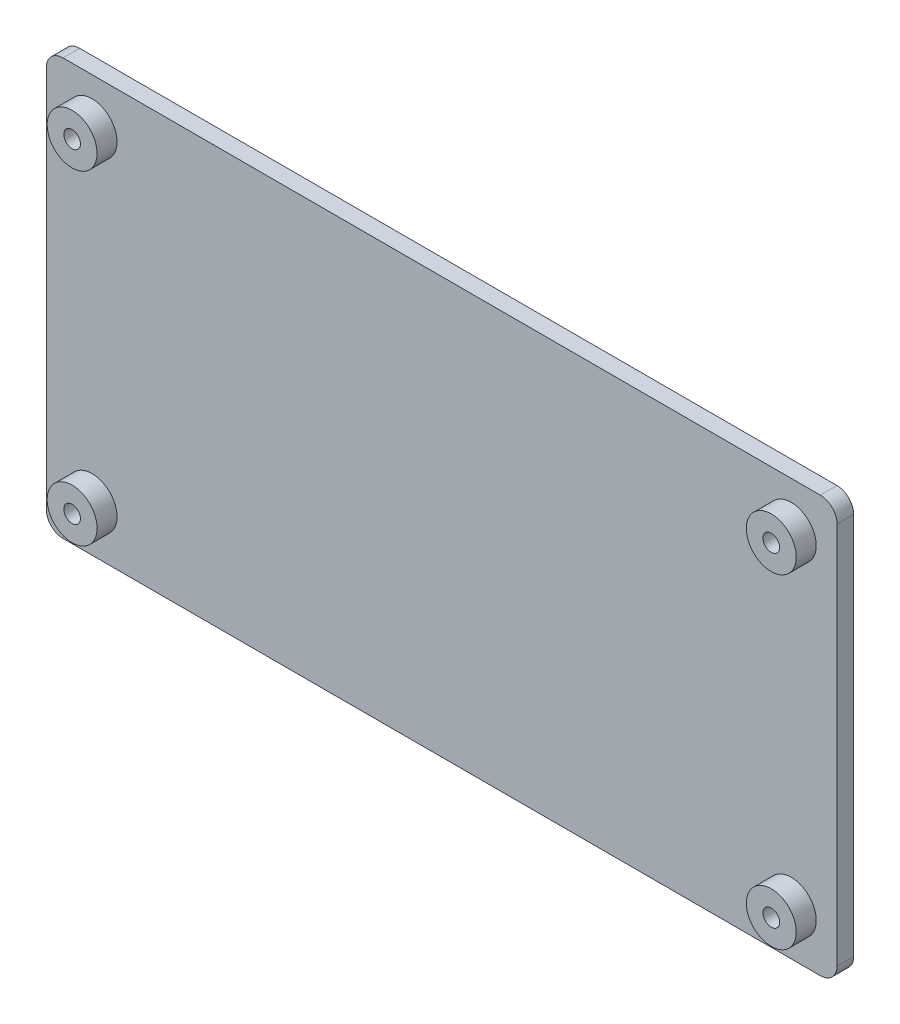
SolidWorks part; units mm, degrees
ref_plane "前视基准面" through (0, 0, 0) normal (0, 0, 1) x (1, 0, 0)
ref_plane "上视基准面" through (0, 0, 0) normal (0, 1, 0) x (1, 0, 0)
ref_plane "右视基准面" through (0, 0, 0) normal (1, 0, 0) x (0, 0, -1)
sketch "草图1" plane through (0, 0, 0) normal (0, 0, 1) x (1, 0, 0)
  line L1 (-47.5, -25) -> (47.5, -25)
  line L2 (-47.5, -25) -> (-47.5, 25)
  line L3 (-47.5, 25) -> (47.5, 25)
  line L4 (47.5, -25) -> (47.5, 25)
  line L5 (0, 25) -> (0, -25) construction
  line L6 (-47.5, 0) -> (47.5, 0) construction
  point P0 (0, 0)
extrude "凸台-拉伸1" add sketch "草图1" along normal blind 2
sketch "草图3" plane through (0, 0, 0) normal (0, 0, -1) x (-1, 0, 0)
  circle A7 centre (42.0002, 19.5001) radius 2 construction
  circle A10 centre (42.0002, -19.5) radius 2 construction
  circle A15 centre (-42, -19.5) radius 2 construction
  circle A18 centre (-42, 19.5001) radius 2 construction
  circle A20 centre (-42, 19.5001) radius 3
  circle A21 centre (42.0002, 19.5001) radius 3
  circle A22 centre (42.0002, -19.5) radius 3
  circle A23 centre (-42, -19.5) radius 3
  dimension "D1" = 1
  dimension "D2" = 1
  dimension "D3" = 1
  dimension "D4" = 1
extrude "凸台-拉伸3" add sketch "草图3" against normal blind 2.4 from offset 2 offset against normal yes
sketch "草图4" plane through (0, 0, 0) normal (0, 0, -1) x (-1, 0, 0)
  circle A2 centre (-42, 19.5001) radius 2
  circle A3 centre (-42, -19.5) radius 2
  circle A5 centre (42.0002, 19.5001) radius 2
  circle A7 centre (42.0002, -19.5) radius 2
extrude "切除-拉伸1" cut sketch "草图4" against normal blind 1.5
sketch "草图5" plane through (0, 0, 0) normal (0, 0, -1) x (-1, 0, 0)
  circle A0 centre (-42, 19.5001) radius 1
  circle A1 centre (42.0002, 19.5001) radius 1
  circle A2 centre (42.0002, -19.5) radius 1
  circle A3 centre (-42, -19.5) radius 1
  point P12 (0, 0)
extrude "切除-拉伸2" cut sketch "草图5" against normal through all
fillet "圆角2" radius 2 4 edges at (47.5, -25, 1) (47.5, 25, 1) (-47.5, -25, 1) (-47.5, 25, 1)
